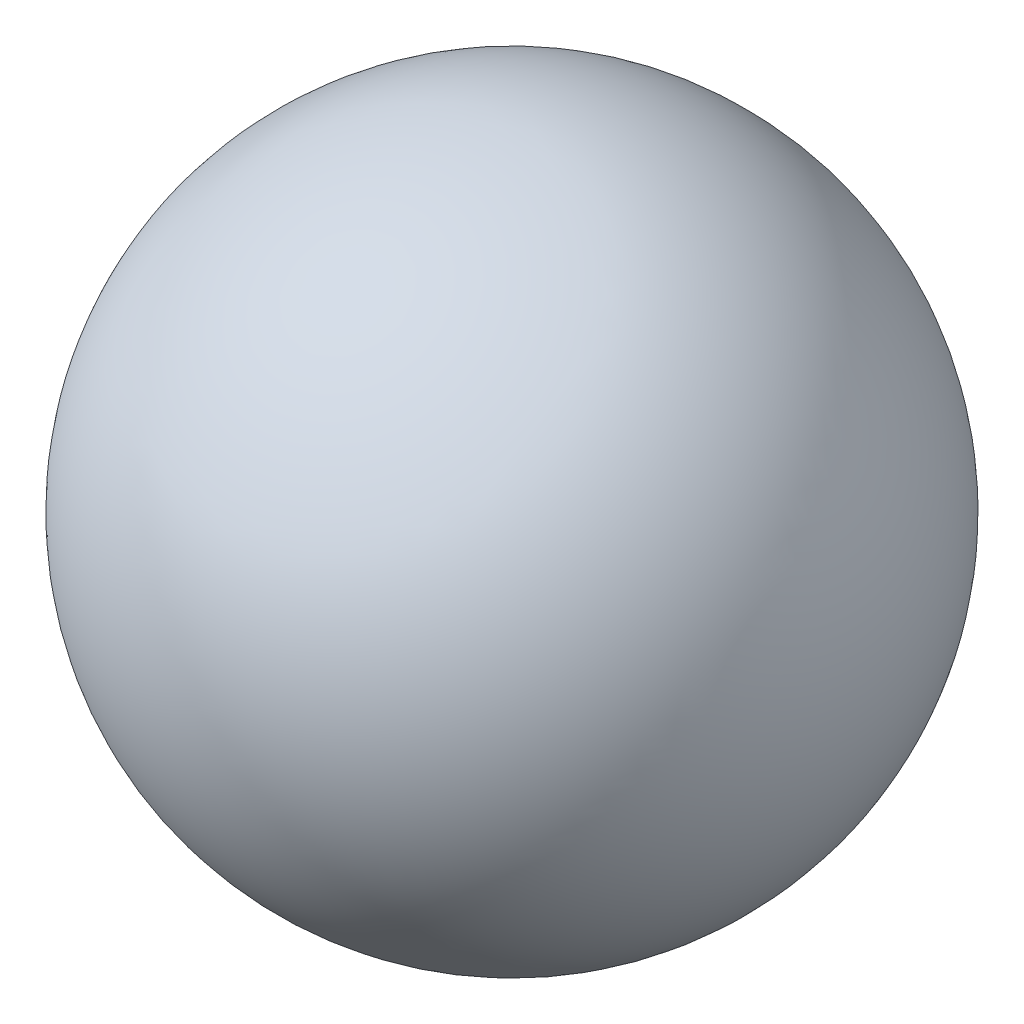
SolidWorks part; units mm, degrees
ref_plane "Ebene vorne" through (0, 0, 0) normal (0, 0, 1) x (1, 0, 0)
ref_plane "Ebene oben" through (0, 0, 0) normal (0, 1, 0) x (1, 0, 0)
ref_plane "Ebene rechts" through (0, 0, 0) normal (1, 0, 0) x (0, 0, -1)
ref_plane "Plane1" through (0, 0, 0) normal (0, 0, 1) x (1, 0, 0)
sketch "Sketch1" plane through (0, 0, 0) normal (0, 0, 1) x (1, 0, 0)
  line L0 (2.1, 2.95) -> (0.9, 2.95)
  line L1 (2.1, 2.95) -> (0.9, 2.95) construction
  arc A0 (0.9, 2.95) -> (2.1, 2.95) centre (1.5, 2.95) cw
revolve "Revolve1" add sketch "Sketch1" angle 360 about L1
